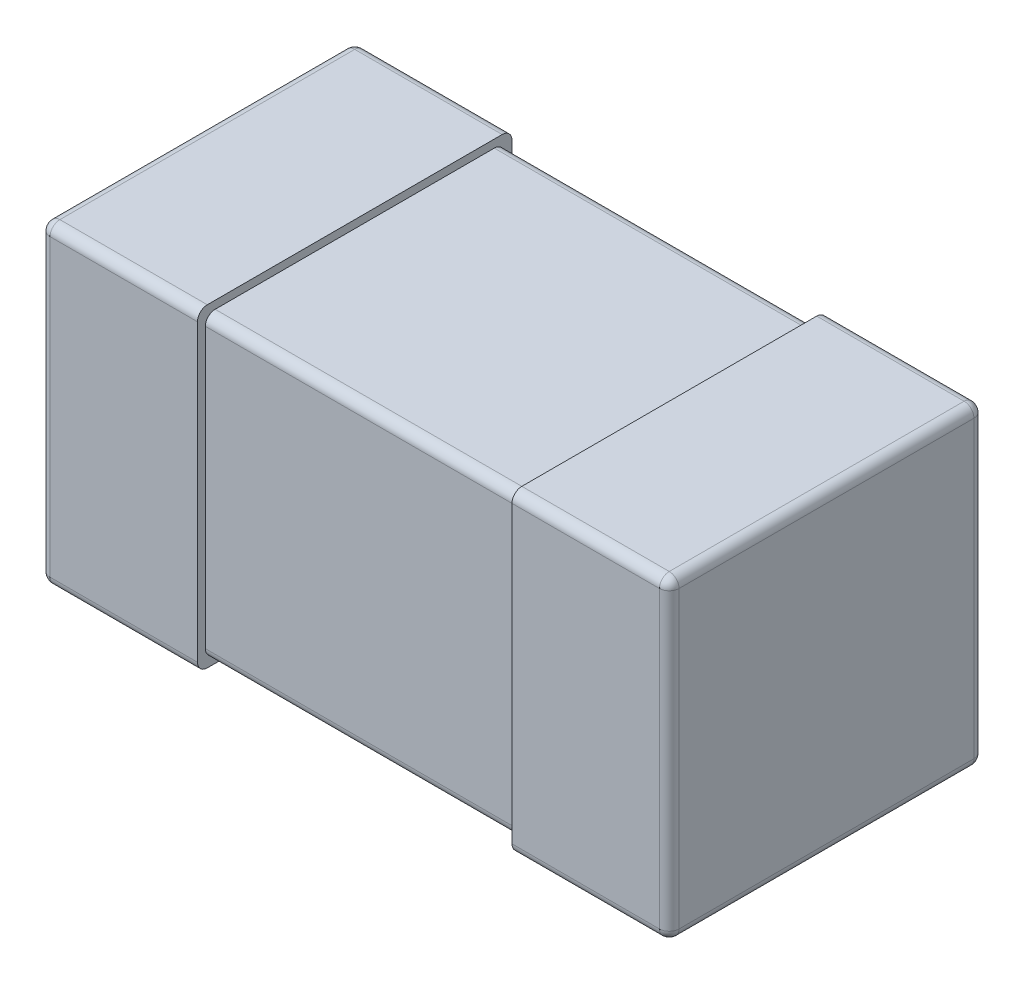
SolidWorks part; units mm, degrees
ref_plane "Спереди" through (0, 0, 0) normal (0, 0, 1) x (1, 0, 0)
ref_plane "Сверху" through (0, 0, 0) normal (0, 1, 0) x (1, 0, 0)
ref_plane "Справа" through (0, 0, 0) normal (1, 0, 0) x (0, 0, -1)
sketch "Эскиз3" plane through (0, 0, 0) normal (0, 0, 1) x (1, 0, 0)
  line L0 (0, 0.7005) -> (0, -0.7992) construction
  line L1 (0.8, 0.4) -> (0.8, -0.4)
  line L2 (0.8, 0.4) -> (0.4, 0.4)
  line L3 (0.4, 0.4) -> (0.4, -0.4)
  line L4 (0.8, -0.4) -> (0.4, -0.4)
  line L5 (-0.8, 0.4) -> (-0.4, 0.4)
  line L6 (-0.8, 0.4) -> (-0.8, -0.4)
  line L7 (-0.8, -0.4) -> (-0.4, -0.4)
  line L8 (-0.4, 0.4) -> (-0.4, -0.4)
  line L9 (-0.8, -0.4) -> (-0.4, 0.4) construction
  line L10 (-0.8, 0.4) -> (-0.4, -0.4) construction
  line L11 (0, 0) -> (-0.6, 0) construction
  point P11 (-0.6, 0)
  dimension "D1" = 0.4
  dimension "D2" = 0.8
  dimension "D3" = 1.6
extrude "Вытянуть3" add sketch "Эскиз3" along normal blind 0.8
sketch "Эскиз4" plane through (0, 0, 0) normal (0, 0, 1) x (1, 0, 0)
  line L1 (0.4, -0.38) -> (-0.4, -0.38)
  line L2 (0.4, -0.38) -> (0.4, 0.38)
  line L3 (0.4, 0.38) -> (-0.4, 0.38)
  line L4 (-0.4, -0.38) -> (-0.4, 0.38)
  line L5 (0.4, -0.38) -> (-0.4, 0.38) construction
  line L6 (0.4, 0.38) -> (-0.4, -0.38) construction
  line L7 (-0.4, -0.4) -> (-0.4, 0.4) construction
  point P0 (0, 0)
  dimension "D1" = 0.02
extrude "Бобышка-Вытянуть3" add sketch "Эскиз4" along normal offset from surface (0.76 mm away) 0.02 from offset 0.02 up to face at (-0.6, 0, 0.8)
fillet "Скругление2" radius 0.025 16 edges at (-0.8, 0.4, 0.4) (-0.8, 0, 0.8) (-0.8, -0.4, 0.4) (-0.8, 0, 0) (-0.6, 0.4, 0) (-0.6, -0.4, 0) (-0.6, 0.4, 0.8) (-0.6, -0.4, 0.8) (0.8, -0.4, 0.4) (0.8, 0, 0.8) (0.8, 0.4, 0.4) (0.8, 0, 0) (0.6, 0.4, 0) (0.6, 0.4, 0.8) (0.6, -0.4, 0.8) (0.6, -0.4, 0)
fillet "Скругление3" radius 0.025 4 edges at (0, -0.38, 0.02) (0, 0.38, 0.02) (0, 0.38, 0.78) (0, -0.38, 0.78)
